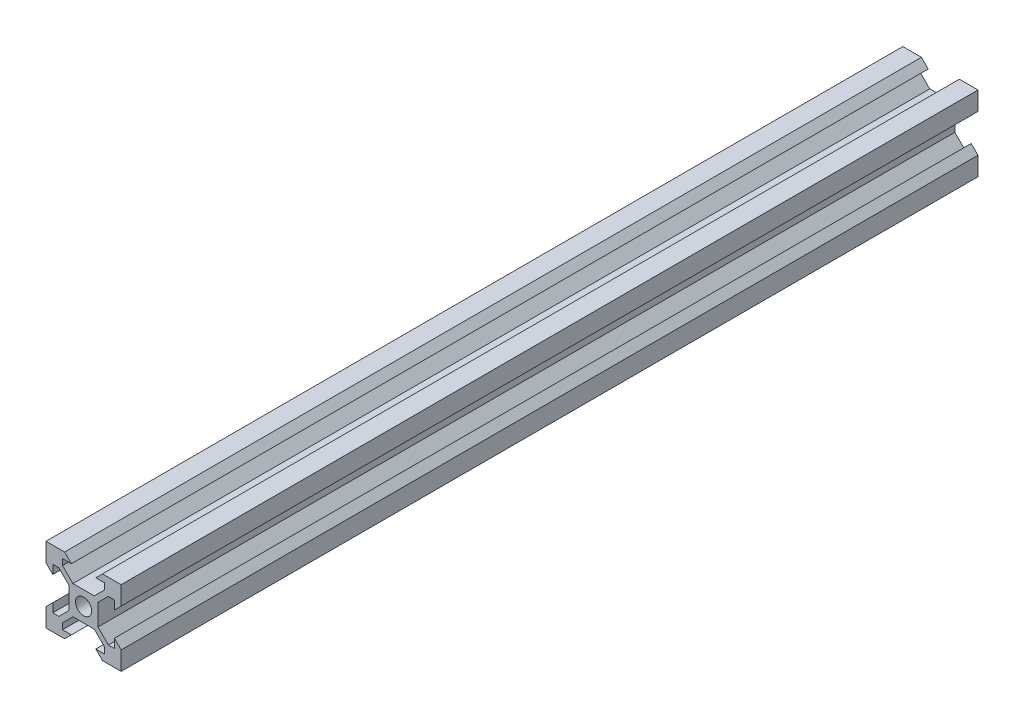
SolidWorks part; units mm, degrees
ref_plane "Alzado" through (0, 0, 0) normal (0, 0, 1) x (1, 0, 0)
ref_plane "Planta" through (0, 0, 0) normal (0, 1, 0) x (1, 0, 0)
ref_plane "Vista lateral" through (0, 0, 0) normal (1, 0, 0) x (0, 0, -1)
sketch "Croquis1" plane through (0, 0, 0) normal (0, 0, 1) x (1, 0, 0)
  line L58 (-1.915, -1.915) -> (-2.8, -2.8) construction
  line L66 (0, 0) -> (-1.915, 0)
  line L72 (0, 0) -> (0, -1.915)
  line L73 (-2.52, -5) -> (-5, -5)
  line L74 (-5, -2.525) -> (-5, -5)
  line L79 (-1.42, -1.915) -> (-2.8, -3.295)
  line L80 (-5, -5) -> (-2.8, -5)
  line L81 (-5, -5) -> (-5, -2.8)
  line L82 (-4.1, -2.8) -> (-3.295, -2.8)
  line L83 (-2.8, -4.1) -> (-2.8, -3.295)
  line L84 (0, 0) -> (-1.915, 0)
  line L85 (0, 0) -> (0, -1.915)
  line L86 (0, -1.915) -> (-1.42, -1.915)
  line L87 (-1.915, 0) -> (-1.915, -1.42)
  line L88 (-1.915, -1.42) -> (-3.295, -2.8)
  line L90 (-1.6675, -2.1625) -> (-2.5525, -3.0475) construction
  line L91 (-2.1625, -1.6675) -> (-3.0475, -2.5525) construction
  line L92 (-5, -2.8) -> (-5, -2.525)
  line L93 (-5, -2.525) -> (-4.1, -1.625)
  line L94 (-4.1, -1.625) -> (-4.1, -2.8)
  line L95 (-2.8, -5) -> (-2.52, -5)
  line L96 (-2.52, -5) -> (-1.62, -4.1)
  line L97 (-1.62, -4.1) -> (-2.8, -4.1)
  line L98 (0, 0) -> (0, 1.915)
  line L99 (0, 0) -> (-1.915, 0)
  line L100 (-5, 2.52) -> (-5, 5)
  line L101 (-2.525, 5) -> (-5, 5)
  line L102 (-1.915, 1.42) -> (-3.295, 2.8)
  line L103 (-5, 5) -> (-5, 2.8)
  line L104 (-5, 5) -> (-2.8, 5)
  line L105 (-2.8, 4.1) -> (-2.8, 3.295)
  line L106 (-4.1, 2.8) -> (-3.295, 2.8)
  line L107 (0, 0) -> (0, 1.915)
  line L108 (0, 0) -> (-1.915, 0)
  line L109 (-1.915, 0) -> (-1.915, 1.42)
  line L110 (0, 1.915) -> (-1.42, 1.915)
  line L111 (-1.42, 1.915) -> (-2.8, 3.295)
  line L112 (-2.8, 5) -> (-2.525, 5)
  line L113 (-2.525, 5) -> (-1.625, 4.1)
  line L114 (-1.625, 4.1) -> (-2.8, 4.1)
  line L115 (-5, 2.8) -> (-5, 2.52)
  line L116 (-5, 2.52) -> (-4.1, 1.62)
  line L117 (-4.1, 1.62) -> (-4.1, 2.8)
  line L118 (-1.915, 1.915) -> (-2.8, 2.8) construction
  line L119 (0, 0) -> (1.915, 0)
  line L120 (0, 0) -> (0, 1.915)
  line L121 (2.52, 5) -> (5, 5)
  line L122 (5, 2.525) -> (5, 5)
  line L123 (1.42, 1.915) -> (2.8, 3.295)
  line L124 (5, 5) -> (2.8, 5)
  line L125 (5, 5) -> (5, 2.8)
  line L126 (4.1, 2.8) -> (3.295, 2.8)
  line L127 (2.8, 4.1) -> (2.8, 3.295)
  line L128 (0, 0) -> (1.915, 0)
  line L129 (0, 0) -> (0, 1.915)
  line L130 (0, 1.915) -> (1.42, 1.915)
  line L131 (1.915, 0) -> (1.915, 1.42)
  line L132 (1.915, 1.42) -> (3.295, 2.8)
  line L133 (5, 2.8) -> (5, 2.525)
  line L134 (5, 2.525) -> (4.1, 1.625)
  line L135 (4.1, 1.625) -> (4.1, 2.8)
  line L136 (2.8, 5) -> (2.52, 5)
  line L137 (2.52, 5) -> (1.62, 4.1)
  line L138 (1.62, 4.1) -> (2.8, 4.1)
  line L139 (1.915, 1.915) -> (2.8, 2.8) construction
  line L140 (0, 0) -> (0, -1.915)
  line L141 (0, 0) -> (1.915, 0)
  line L142 (5, -2.52) -> (5, -5)
  line L143 (2.525, -5) -> (5, -5)
  line L144 (1.915, -1.42) -> (3.295, -2.8)
  line L145 (5, -5) -> (5, -2.8)
  line L146 (5, -5) -> (2.8, -5)
  line L147 (2.8, -4.1) -> (2.8, -3.295)
  line L148 (4.1, -2.8) -> (3.295, -2.8)
  line L149 (0, 0) -> (0, -1.915)
  line L150 (0, 0) -> (1.915, 0)
  line L151 (1.915, 0) -> (1.915, -1.42)
  line L152 (0, -1.915) -> (1.42, -1.915)
  line L153 (1.42, -1.915) -> (2.8, -3.295)
  line L154 (2.8, -5) -> (2.525, -5)
  line L155 (2.525, -5) -> (1.625, -4.1)
  line L156 (1.625, -4.1) -> (2.8, -4.1)
  line L157 (5, -2.8) -> (5, -2.52)
  line L158 (5, -2.52) -> (4.1, -1.62)
  line L159 (4.1, -1.62) -> (4.1, -2.8)
  line L160 (1.915, -1.915) -> (2.8, -2.8) construction
  circle A3 centre (0, 0) radius 1.075
  circle A4 centre (0, 0) radius 1.075
  circle A5 centre (0, 0) radius 1.075
  circle A6 centre (0, 0) radius 1.075
  point P83 (0, 0)
  dimension "D3" = 2.15
  dimension "D20" = 0.9
  dimension "D5" = 10
  dimension "D4" = 4
  dimension "D10" = 2.2
  dimension "D6" = 10
  dimension "D14" = 1.915
  dimension "D15" = 0.35
  dimension "D17" = 0.35
  dimension "D18" = 1.175
  dimension "D21" = 0.275
  dimension "D22" = 0.9
  dimension "D23" = 0.28
  dimension "D24" = 1.18
extrude "Saliente-Extruir1" add sketch "Croquis1" along normal blind 114 contours A3 L129 L110 L111 L105 L114 L113 L101 L100 L116 L117 L106 L102 L109 L108 | A3 L150 L131 L132 L126 L135 L134 L122 L121 L137 L138 L127 L123 L130 L129 | A3 L149 L152 L153 L147 L156 L155 L143 L142 L158 L159 L148 L144 L151 L150 | A3 L108 L87 L88 L82 L94 L93 L74 L73 L96 L97 L83 L79 L86 L149
